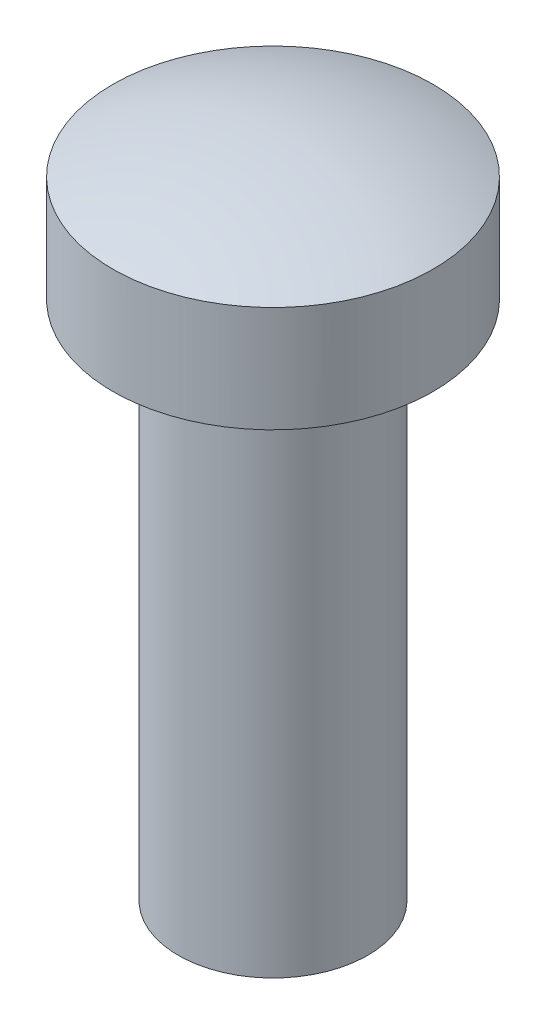
SolidWorks part; units mm, degrees
ref_plane "前基準面" through (0, 0, 0) normal (0, 0, 1) x (1, 0, 0)
ref_plane "上基準面" through (0, 0, 0) normal (0, 1, 0) x (1, 0, 0)
ref_plane "右基準面" through (0, 0, 0) normal (1, 0, 0) x (0, 0, -1)
sketch "草圖1" plane through (0, 0, 0) normal (0, 0, 1) x (1, 0, 0)
  line L0 (0, 0) -> (0, 3.4882)
  line L2 (-0.8453, 2.75) -> (-0.5, 2.75)
  line L3 (-0.5, 2.75) -> (-0.5, 0)
  line L4 (-0.5, 0) -> (0, 0)
  line L5 (-0.8453, 2.75) -> (-0.8453, 3.3093)
  arc A0 (0, 3.4882) -> (-0.8453, 3.3093) centre (0, 1.4021) ccw
  dimension "D4" = 2.0862
  dimension "D1" = 0.5
  dimension "D2" = 2.75
  dimension "D3" = 0.8453
  dimension "D5" = 0.7382
revolve "旋轉1" add sketch "草圖1" angle 360 about L0
cosmetic thread "裝飾螺紋線1"
